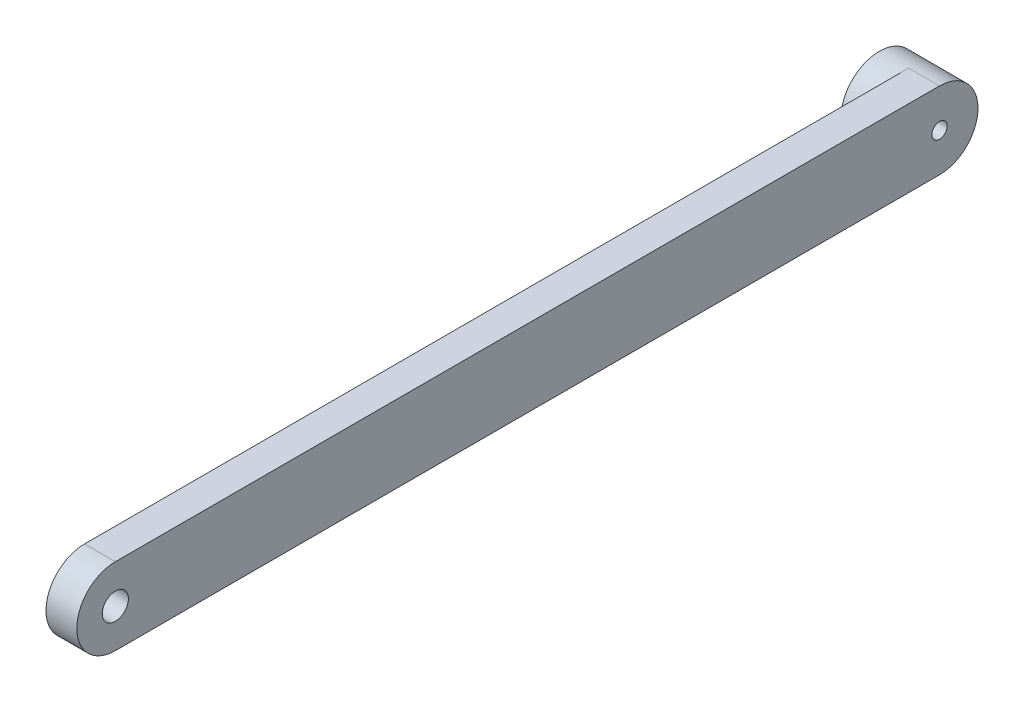
SolidWorks part; units mm, degrees
ref_plane "Plano frontal" through (0, 0, 0) normal (0, 0, 1) x (1, 0, 0)
ref_plane "Plano superior" through (0, 0, 0) normal (0, 1, 0) x (1, 0, 0)
ref_plane "Plano direito" through (0, 0, 0) normal (1, 0, 0) x (0, 0, -1)
sketch "Esboço1" plane through (0, 0, 0) normal (1, 0, 0) x (0, 0, -1)
  line L0 (0, 0) -> (53.5, 0) construction
  line L1 (0, 2.5) -> (53.5, 2.5)
  line L2 (0, -2.5) -> (53.5, -2.5)
  arc A0 (0, 2.5) -> (0, -2.5) centre (0, 0) ccw
  arc A1 (53.5, -2.5) -> (53.5, 2.5) centre (53.5, 0) ccw
  point P3 (26.75, 0)
  dimension "D1" = 5
  dimension "D2" = 53.5
extrude "Ressalto-extrusão1" add sketch "Esboço1" along normal blind 2
sketch "Esboço2" plane through (2, 0, 0) normal (1, 0, 0) x (0, 0, -1)
  circle A0 centre (0, 0) radius 0.85
  dimension "D1" = 1.7
extrude "Corte-extrusão1" cut sketch "Esboço2" against normal up to next
sketch "Esboço4" plane through (0, 0, 0) normal (-1, 0, 0) x (0, 0, 1)
  circle A0 centre (-53.5, 0) radius 2.5
  arc A1 (-53.5, 2.5) -> (-53.5, -2.5) centre (-53.5, 0) ccw construction
extrude "Ressalto-extrusão2" add sketch "Esboço4" along normal blind 1.9
sketch "Esboço3" plane through (2, 0, 0) normal (1, 0, 0) x (0, 0, -1)
  circle A0 centre (53.5, 0) radius 0.5
  arc A1 (53.5, -2.5) -> (53.5, 2.5) centre (53.5, 0) ccw construction
  dimension "D1" = 1
extrude "Corte-extrusão2" cut sketch "Esboço3" against normal up to next
